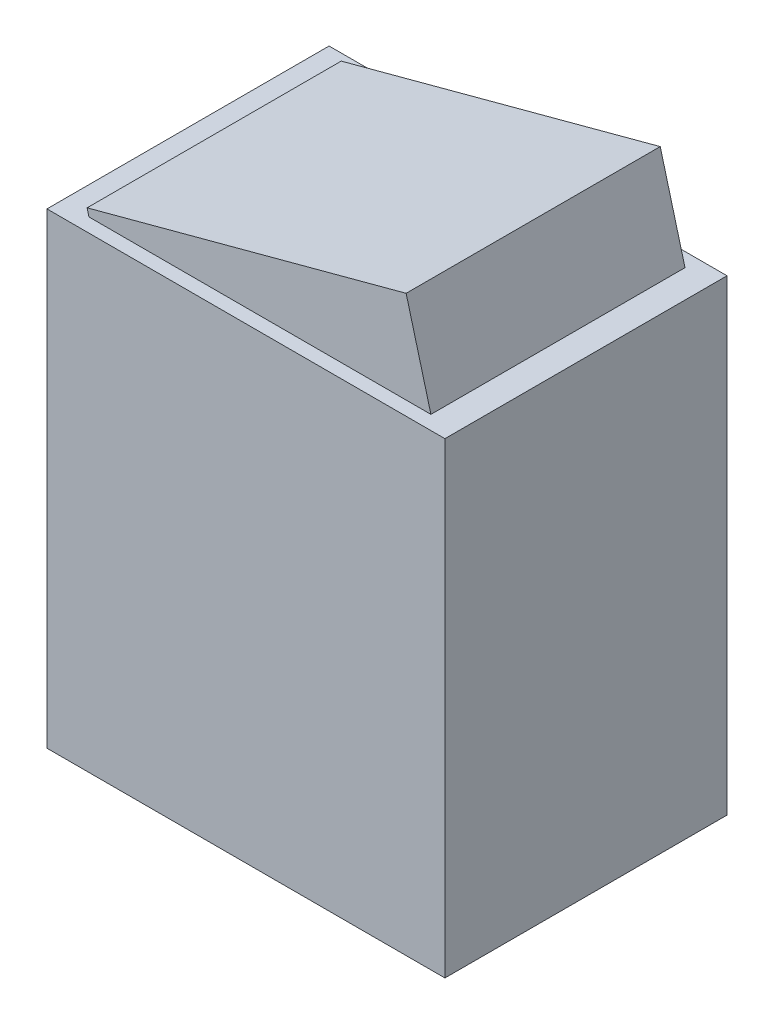
SolidWorks part; units mm, degrees
ref_plane "Front Plane" through (0, 0, 0) normal (0, 0, 1) x (1, 0, 0)
ref_plane "Top Plane" through (0, 0, 0) normal (0, 1, 0) x (1, 0, 0)
ref_plane "Right Plane" through (0, 0, 0) normal (1, 0, 0) x (0, 0, -1)
sketch "Sketch1" plane through (0, 0, 0) normal (0, 1, 0) x (1, 0, 0)
  line L1 (-10.65, 7.55) -> (10.65, 7.55)
  line L2 (-10.65, 7.55) -> (-10.65, -7.55)
  line L3 (-10.65, -7.55) -> (10.65, -7.55)
  line L4 (10.65, 7.55) -> (10.65, -7.55)
  line L5 (-10.65, 7.55) -> (10.65, -7.55) construction
  line L6 (-10.65, -7.55) -> (10.65, 7.55) construction
  point P0 (0, 0)
  dimension "D1" = 15.1
  dimension "D2" = 21.3
extrude "Boss-Extrude1" add sketch "Sketch1" along normal blind 25
sketch "Sketch2" plane through (0, 25, 0) normal (0, 1, 0) x (1, 0, 0)
  line L0 (-10.65, 7.55) -> (-10.65, -7.55) construction
  line L1 (-9.15, 6.8) -> (9.15, 6.8)
  line L2 (-9.15, 6.8) -> (-9.15, -6.8)
  line L3 (-9.15, -6.8) -> (9.15, -6.8)
  line L4 (9.15, 6.8) -> (9.15, -6.8)
  line L5 (-9.15, 6.8) -> (9.15, -6.8) construction
  line L6 (-9.15, -6.8) -> (9.15, 6.8) construction
  line L8 (10.65, 7.55) -> (-10.65, 7.55) construction
  point P0 (0, 0)
  dimension "D1" = 1.5
  dimension "D2" = 0.75
ref_plane "Plane1" through (-6.9634, 25.9878, 0) normal (-0.2588, 0.9659, 0) x (0, 0, 1)
sketch "Sketch4" plane through (-6.9634, 25.9878, 0) normal (-0.2588, 0.9659, 0) x (0, 0, 1)
  line L0 (-6.8, -2.3677) -> (6.8, -2.3677)
  line L1 (6.8, -2.3677) -> (6.8, 15.3087)
  line L2 (6.8, 15.3087) -> (-6.8, 15.3087)
  line L3 (-6.8, 15.3087) -> (-6.8, -2.3677)
  line L6 (-6.8, -2.3677) -> (-6.8, 15.3087) construction
  line L7 (6.8, -2.3677) -> (6.8, 15.3087) construction
  line L11 (-6.8, -2.3677) -> (6.8, -2.3677) construction
  line L12 (-6.8, 15.3087) -> (6.8, 15.3087) construction
  point P2 (0, 0)
  point P4 (0, 0)
  point P9 (0, 0)
extrude "Boss-Extrude2" add sketch "Sketch4" against normal up to surface (5.1246 mm away)
